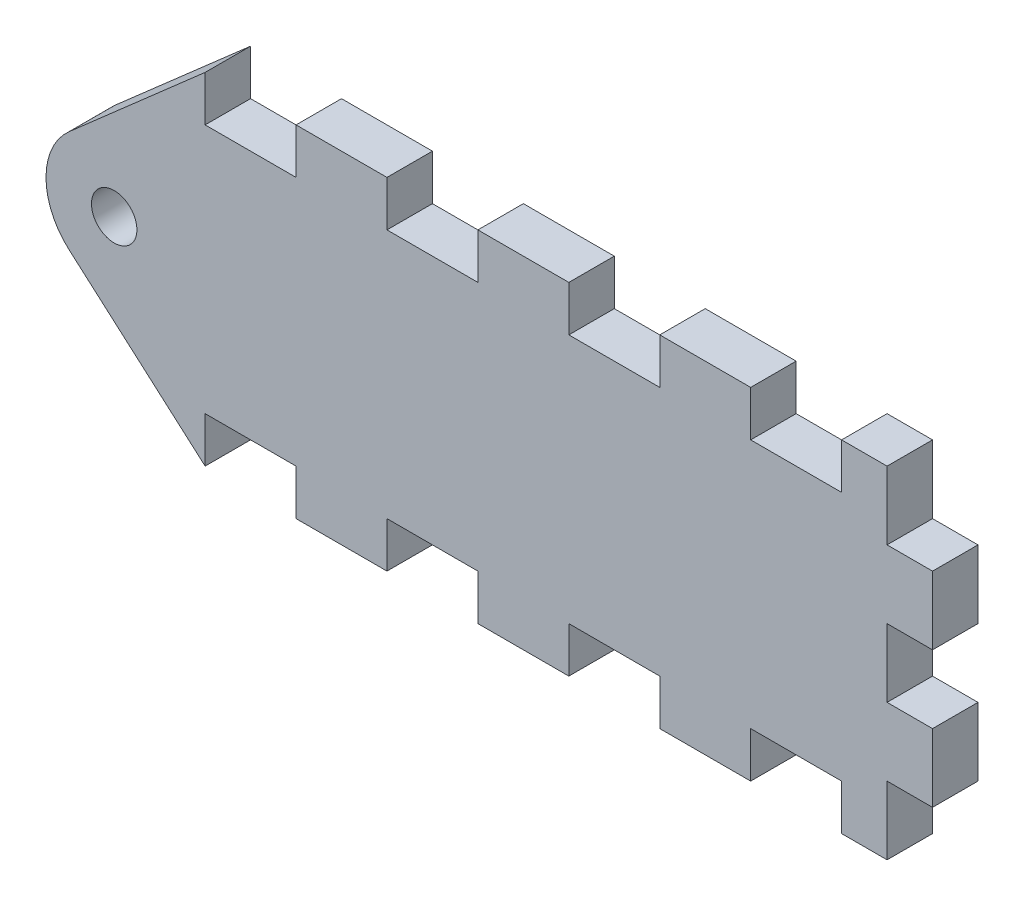
SolidWorks part; units mm, degrees
ref_plane "Front Plane" through (0, 0, 0) normal (0, 0, 1) x (1, 0, 0)
ref_plane "Top Plane" through (0, 0, 0) normal (0, 1, 0) x (1, 0, 0)
ref_plane "Right Plane" through (0, 0, 0) normal (1, 0, 0) x (0, 0, -1)
sketch "Sketch1" plane through (0, 0, 0) normal (0, 0, 1) x (1, 0, 0)
  line L0 (-50.8, 0) -> (-63.5, 0) construction
  line L1 (-50.8, -23.8125) -> (50.8, -23.8125)
  line L2 (-50.8, -23.8125) -> (-50.8, 23.8125) construction
  line L3 (-50.8, 23.8125) -> (50.8, 23.8125)
  line L4 (50.8, -23.8125) -> (50.8, 23.8125)
  line L5 (-50.8, -23.8125) -> (50.8, 23.8125) construction
  line L6 (-50.8, 23.8125) -> (50.8, -23.8125) construction
  line L7 (-50.8, 23.8125) -> (-69.7815, 7.1602)
  line L8 (-50.8, -23.8125) -> (-69.7815, -7.1602)
  arc A0 (-69.7815, 7.1602) -> (-69.7815, -7.1602) centre (-63.5, 0) ccw
  point P0 (0, 0)
  dimension "D1" = 47.625
  dimension "D2" = 101.6
  dimension "D3" = 12.7
extrude "Mass" add sketch "Sketch1" along normal blind 6.35
sketch "Sketch3" plane through (0, 0, 0) normal (0, 0, -1) x (-1, 0, 0)
  line L1 (-50.8, 23.8125) -> (50.8, 23.8125) construction
  line L2 (50.8, -23.8125) -> (-50.8, -23.8125) construction
  line L3 (-50.8, 23.8125) -> (-38.1, 23.8125) construction
  line L5 (-25.4, 17.4625) -> (-38.1, 17.4625)
  line L6 (-25.4, 17.4625) -> (-25.4, 30.1625)
  line L7 (-25.4, 30.1625) -> (-38.1, 30.1625)
  line L8 (-38.1, 17.4625) -> (-38.1, 30.1625)
  line L9 (-25.4, 17.4625) -> (-38.1, 30.1625) construction
  line L10 (-25.4, 30.1625) -> (-38.1, 17.4625) construction
  line L11 (-25.4, -30.1625) -> (-38.1, -30.1625)
  line L12 (-25.4, -30.1625) -> (-25.4, -17.4625)
  line L13 (-25.4, -17.4625) -> (-38.1, -17.4625)
  line L14 (-38.1, -30.1625) -> (-38.1, -17.4625)
  line L15 (-25.4, -30.1625) -> (-38.1, -17.4625) construction
  line L16 (-25.4, -17.4625) -> (-38.1, -30.1625) construction
  point P3 (-31.75, 23.8125)
  point P4 (-31.75, -23.8125)
  dimension "D1" = 12.7
  dimension "D2" = 12.7
  dimension "D3" = 12.7
sketch "Sketch4" plane through (0, 0, 0) normal (0, 0, -1) x (-1, 0, 0)
  circle A0 centre (63.5, 0) radius 3.175
  dimension "D1" = 6.35
extrude "Cut-Extrude1" cut sketch "Sketch4" against normal through all
extrude "Cut-Extrude2" cut sketch "Sketch3" against normal through all
pattern_linear "LPattern1" count 4 spacing 25.4 along (-1, 0, 0) of "Cut-Extrude2"
sketch "Sketch5" plane through (0, 0, 0) normal (0, 0, -1) x (-1, 0, 0)
  line L0 (-50.8, -23.8125) -> (-50.8, 23.8125) construction
  line L1 (-57.15, 4.7625) -> (-44.45, 4.7625)
  line L2 (-57.15, 4.7625) -> (-57.15, -4.7625)
  line L3 (-57.15, -4.7625) -> (-44.45, -4.7625)
  line L4 (-44.45, 4.7625) -> (-44.45, -4.7625)
  line L5 (-57.15, 4.7625) -> (-44.45, -4.7625) construction
  line L6 (-57.15, -4.7625) -> (-44.45, 4.7625) construction
  point P0 (-50.8, 0)
  dimension "D1" = 9.525
  dimension "D2" = 12.7
extrude "Cut-Extrude3" cut sketch "Sketch5" against normal through all
pattern_linear "LPattern2" count 2 spacing 19.05 along (0, -1, 0) count 2 spacing 19.05 along (0, 1, 0) of "Cut-Extrude3"
